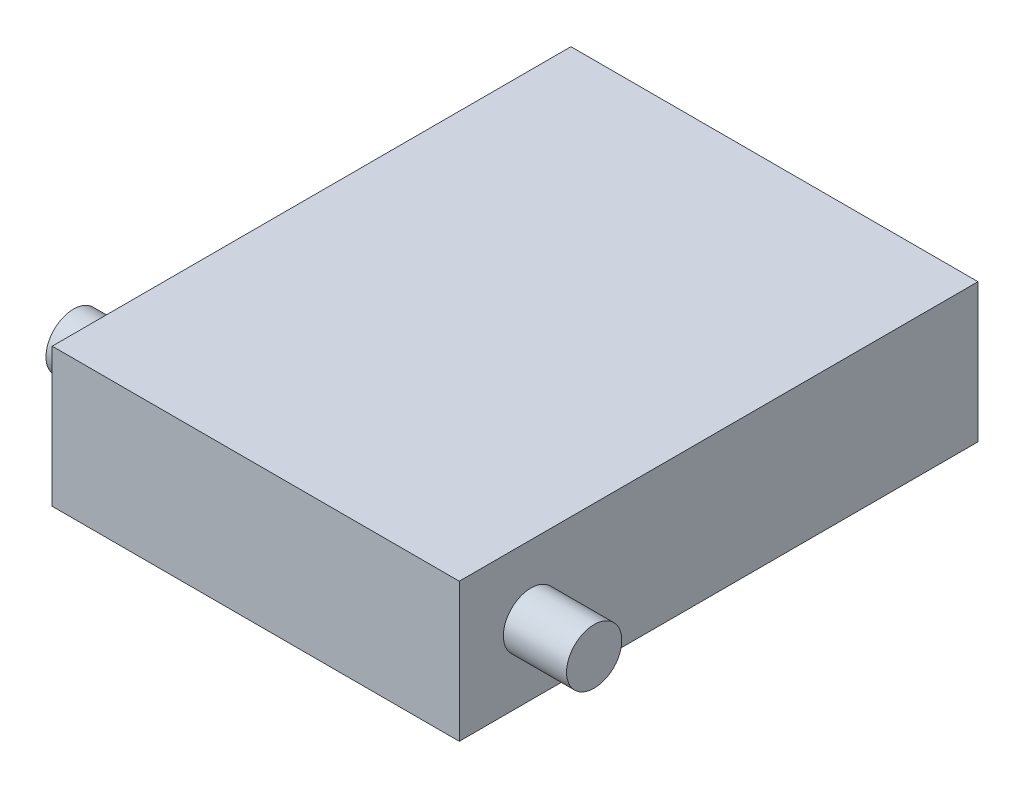
SolidWorks part; units mm, degrees
ref_plane "Front Plane" through (0, 0, 0) normal (0, 0, 1) x (1, 0, 0)
ref_plane "Top Plane" through (0, 0, 0) normal (0, 1, 0) x (1, 0, 0)
ref_plane "Right Plane" through (0, 0, 0) normal (1, 0, 0) x (0, 0, -1)
sketch "Sketch1" plane through (0, 0, 0) normal (0, 1, 0) x (1, 0, 0)
  line L1 (0, 0) -> (20.34, 0)
  line L2 (0, 0) -> (0, -25.92)
  line L3 (0, -25.92) -> (20.34, -25.92)
  line L4 (20.34, 0) -> (20.34, -25.92)
  dimension "D1" = 25.92
  dimension "D2" = 20.34
extrude "Boss-Extrude2" add sketch "Sketch1" against normal blind 6.93 contours L1 L4 L3 L2
sketch "Sketch3" plane through (20.34, 0, 0) normal (1, 0, 0) x (0, 0, -1)
  line L0 (-25.92, -3.465) -> (1.7916, -3.465) construction
  line L1 (-25.92, -6.93) -> (-25.92, 0) construction
  circle A0 centre (-22.3367, -3.465) radius 1.38
extrude "Boss-Extrude3" add sketch "Sketch3" along normal blind 3.158
sketch "Sketch6" plane through (0, 0, 0) normal (-1, 0, 0) x (0, 0, 1)
  line L0 (0, -3.465) -> (25.92, -3.465) construction
  line L1 (0, -6.93) -> (0, 0) construction
  line L2 (25.92, -6.93) -> (25.92, 0) construction
  line L3 (0, 0) -> (25.92, 0) construction
  circle A0 centre (21.6941, -3.465) radius 1.38
  dimension "D1" = 3.465
extrude "Boss-Extrude4" add sketch "Sketch6" along normal blind 3.158
